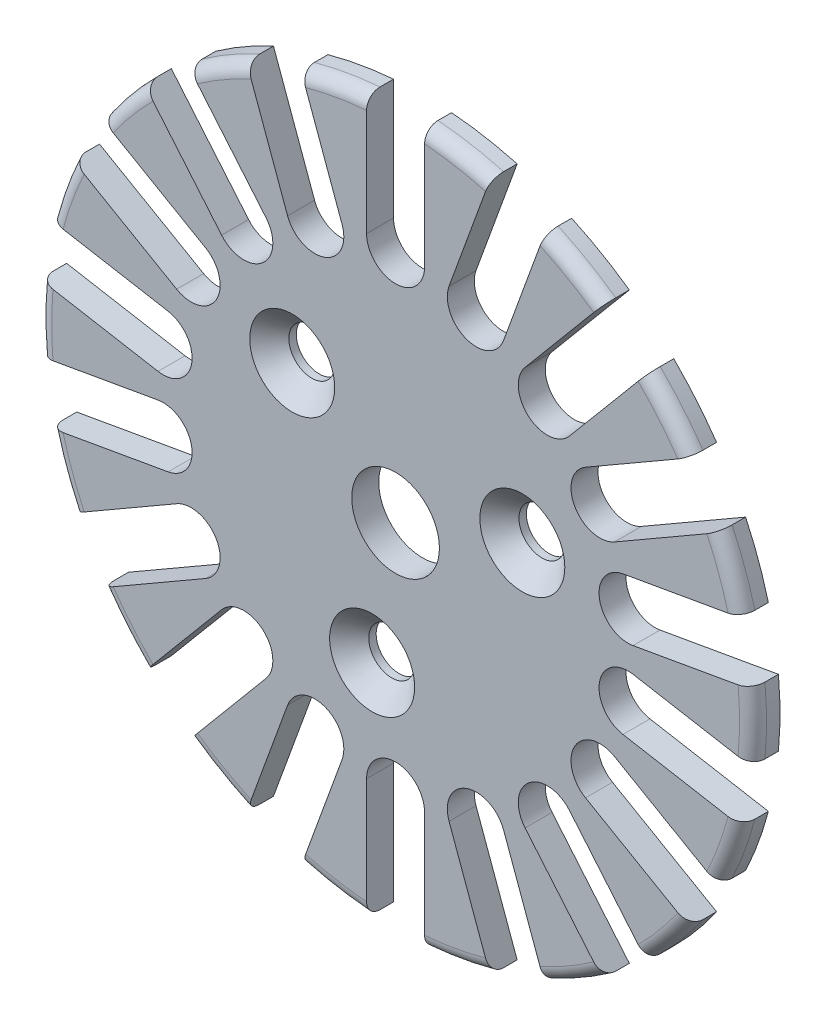
SolidWorks part; units mm, degrees
ref_plane "Front" through (0, 0, 0) normal (0, 0, 1) x (1, 0, 0)
ref_plane "Top" through (0, 0, 0) normal (0, 1, 0) x (1, 0, 0)
ref_plane "Right" through (0, 0, 0) normal (1, 0, 0) x (0, 0, -1)
sketch "Sketch1" plane through (0, 0, 0) normal (0, 0, 1) x (1, 0, 0)
  circle A0 centre (0, 0) radius 26.5
  circle A1 centre (0, 0) radius 3.25
  dimension "D1" = 53
  dimension "D2" = 6.5
extrude "Extrude1" add sketch "Sketch1" along normal blind 2
sketch "Sketch2" plane through (0, 0, 2) normal (0, 0, 1) x (1, 0, 0)
  line L0 (2.15, 30.5) -> (2.15, 17.5)
  line L1 (-2.15, 17.5) -> (-2.15, 30.5)
  line L2 (-2.15, 30.5) -> (2.15, 30.5)
  arc A0 (2.15, 17.5) -> (-2.15, 17.5) centre (0, 17.5) cw
  dimension "D2" = 2.15
  dimension "D1" = 4.3
  dimension "D3" = 13
  dimension "D4" = 13
  dimension "D5" = 17.5
extrude "Extrude2" cut sketch "Sketch2" against normal up to surface (2 mm away) up to face at (26.5, 0, 0)
pattern_circular "CirPattern1" count 18 over 360 about axis through (0, 0, 0) along (0, 0, 1) of "Extrude2"
sketch "Sketch3" plane through (0, 0, 2) normal (0, 0, 1) x (1, 0, 0)
  line L0 (0, 0) -> (0, -2.487) construction
  line L1 (-1.7365, -9.8481) -> (0, 0) construction
  circle A0 centre (-1.7365, -9.8481) radius 1.5
  circle A1 centre (0, 0) radius 10 construction
  dimension "D1" = 3
  dimension "D2" = 20
  dimension "D3" = 10
extrude "Extrude3" cut sketch "Sketch3" against normal up to surface (2 mm away) up to face at (0, 0, 0)
pattern_circular "CirPattern2" count 3 over 360 about axis through (0, 0, 0) along (0, 0, 1) of "Extrude3"
fillet "Fillet1" radius 1 18 edges at (4.6017, -26.0974, 2) (13.25, -22.9497, 2) (20.3002, -17.0339, 2) (24.9019, -9.0635, 2) (26.5, 0, 2) (24.9019, 9.0635, 2) (20.3002, 17.0339, 2) (13.25, 22.9497, 2) (4.6017, 26.0974, 2) (-4.6017, 26.0974, 2) (-26.5, 0, 2) (-24.9019, -9.0635, 2) (-20.3002, -17.0339, 2) (-13.25, -22.9497, 2) (-4.6017, -26.0974, 2) (-24.9019, 9.0635, 2) (-13.25, 22.9497, 2) (-20.3002, 17.0339, 2)
hole_wizard "CSK for M3 Flat Head Machine Screw1" positions "Sketch4" profile "Sketch5" countersink size "M3" standard "ANSI Metric"
sketch "Sketch4" plane through (0, 0, 2) normal (0, 0, 1) x (1, 0, 0)
  point P0 (-7.6604, 6.4279)
  point P3 (9.3969, 3.4202)
  point P6 (-1.7365, -9.8481)
sketch "Sketch5" plane through (-7.6604, 6.4279, 2) normal (1, 0, 0) x (0, -1, 0)
  line L0 (0, 0) -> (0, 16.0215)
  line L1 (0, 16.0215) -> (1.7, 15)
  line L2 (1.7, 15) -> (1.7, 1.45)
  line L3 (1.7, 1.45) -> (3.15, 0)
  line L5 (3.15, 0) -> (0, 0)
  line L6 (-1.7, 1.45) -> (-3.15, 0) construction
  line L10 (0, 16.0215) -> (-1.7, 15) construction
  line L11 (0, -6.35) -> (0, 107.95) construction
  dimension "Hole Dia." = 3.4
  dimension "Hole Depth" = 15
  dimension "Near C'Sink Dia." = 6.3
  dimension "Near C'Sink Angle" = 90
  dimension "Drill Angle" = 118
